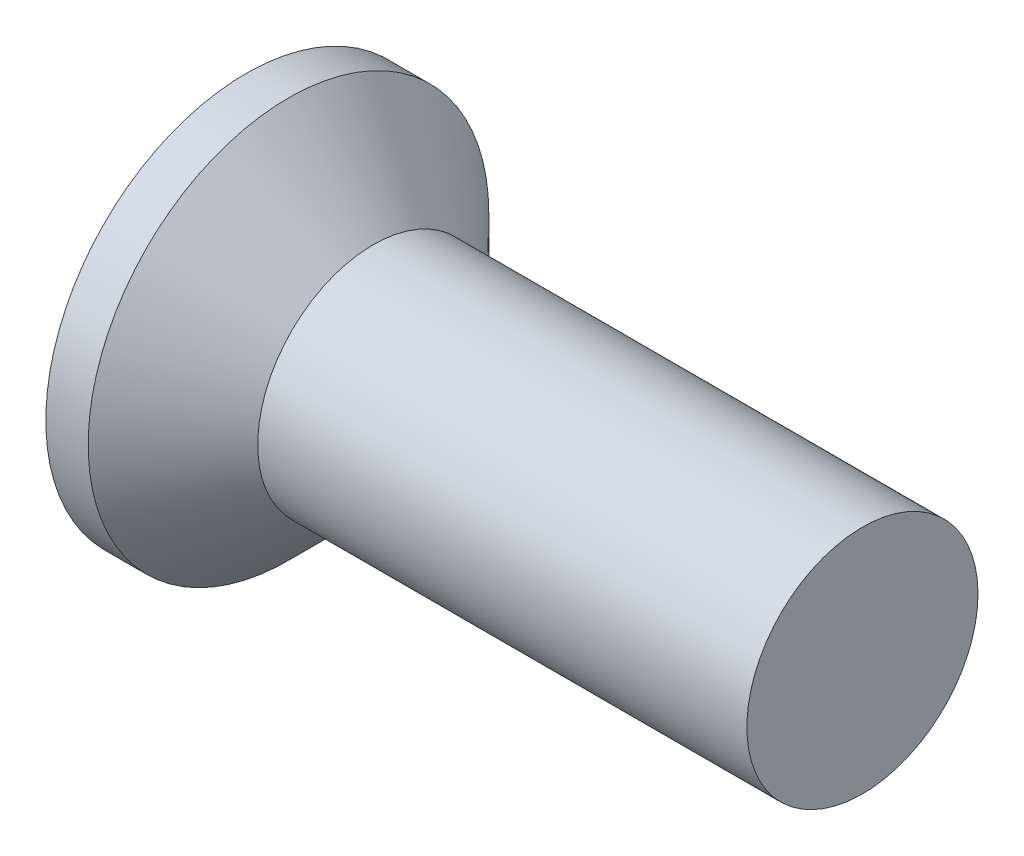
SolidWorks part; units mm, degrees
ref_plane "Front" through (0, 0, 0) normal (0, 0, 1) x (1, 0, 0)
ref_plane "Top" through (0, 0, 0) normal (0, 1, 0) x (1, 0, 0)
ref_plane "Right" through (0, 0, 0) normal (1, 0, 0) x (0, 0, -1)
sketch "Sketch1" plane through (0, 0, 0) normal (0, 0, 1) x (1, 0, 0)
  line L0 (8, 1.5) -> (2.65, 1.5)
  line L1 (2.65, 1.5) -> (1.65, 1.5)
  line L2 (1.65, 1.5) -> (0.55, 2.6)
  line L3 (0.55, 2.6) -> (0, 2.6)
  line L4 (8, 1.5) -> (8, 0)
  line L5 (4.5158, 0) -> (-89.8219, 0) construction
  line L6 (8, 0) -> (0, 0)
  line L7 (0, 2.6) -> (0, 0)
  dimension "D1" = 45
  dimension "d" = 3
  dimension "dk" = 5.2
  dimension "l" = 8
  dimension "k" = 1.65
  dimension "a" = 1
revolve "Base" add sketch "Sketch1" angle 360 about L5
cosmetic thread "ThreadCosmetic1" [suppressed] parameters "bb"=6.35, "THD_MINOR"=2.459
sketch "Sketch6" plane through (0, 0, 0) normal (1, 0, 0) x (0, 0, -1)
  line L0 (-1.9271, 0) -> (2.0512, 0) construction
  line L1 (0, 1.8651) -> (0, -2.0207) construction
  line L2 (0.32, 0.32) -> (0.32, 1.6)
  line L3 (0.32, 1.6) -> (-0.32, 1.6)
  line L4 (-0.32, 0.32) -> (-0.32, 1.6)
  line L5 (0.32, 0.32) -> (1.6, 0.32)
  line L6 (1.6, 0.32) -> (1.6, -0.32)
  line L7 (-1.6, 0.32) -> (-1.6, -0.32)
  line L8 (-0.32, 0.32) -> (-1.6, 0.32)
  line L9 (-0.32, -0.32) -> (-1.6, -0.32)
  line L10 (0.32, -0.32) -> (1.6, -0.32)
  line L11 (-0.32, -0.32) -> (-0.32, -1.6)
  line L12 (0.32, -1.6) -> (-0.32, -1.6)
  line L13 (0.32, -0.32) -> (0.32, -1.6)
  point P16 (-1.6, 0)
  point P17 (1.6, 0)
  dimension "D1" = 0.64
  dimension "m" = 3.2
extrude "CrossRecess" cut sketch "Sketch6" along normal blind 0.825
draft "Draft9" type of draft neutral plane draft angle 30 faces to draft 4 face at (0.4125, 1.6, 0) face at (0.4125, 0, 1.6) face at (0.4125, -1.6, 0) face at (0.4125, 0, -1.6) neutral plane through (0, 2.6, 0) neutral plane normal (-1, 0, 0) parameters "D1"=30
fillet "Fillet5" radius 0.3 4 edges at (0.4125, -0.32, -0.32) (0.4125, 0.32, -0.32) (0.4125, 0.32, 0.32) (0.4125, -0.32, 0.32)
sketch "Sketch7" plane through (0, 0, 0) normal (1, 0, 0) x (0, 0, -1)
  line L0 (-2.0126, 0) -> (1.9757, 0) construction
  line L1 (0, 1.9314) -> (0, -2.0126) construction
  line L2 (0, 0) -> (1.5555, 1.5555) construction
  line L3 (0, 0.4782) -> (1.1314, 1.1314)
  line L4 (-1.5402, 1.5402) -> (0, 0) construction
  line L5 (0.4782, 0) -> (1.1314, 1.1314)
  line L6 (0, -0.4782) -> (1.1314, -1.1314)
  line L7 (0.4782, 0) -> (1.1314, -1.1314)
  line L8 (-0.4782, 0) -> (-1.1314, -1.1314)
  line L9 (0, -0.4782) -> (-1.1314, -1.1314)
  line L10 (-0.4782, 0) -> (-1.1314, 1.1314)
  line L11 (0, 0.4782) -> (-1.1314, 1.1314)
  dimension "D3" = 15
extrude "Cut-Extrude3" [suppressed] cut sketch "Sketch7" along normal blind 10 draft 20
sketch "Sketch8" plane through (0, 0, 0) normal (0, 0, 1) x (1, 0, 0)
  line L0 (-17, 1.7705) -> (-18.25, 1.5)
  line L1 (-18.25, 1.5) -> (1.65, 1.5)
  line L3 (8, -1.5) -> (8, 1.5) construction
  line L6 (1.65, 1.5) -> (1.65, 6.5)
  line L7 (1.65, 6.5) -> (-17, 6.5)
  line L8 (-17, 6.5) -> (-17, 1.7705)
  line L9 (62.4753, 0.2705) -> (52.9594, 0.2705) construction
  dimension "D1" = 5
  dimension "x" = 1.25
  dimension "b" = 25
sketch "Sketch9" plane through (0, 0, 0) normal (0, 0, 1) x (1, 0, 0)
  line L0 (8, 1.2657) -> (8.1353, 1.5)
  line L1 (8.1353, 1.5) -> (8.1353, 1.7705)
  line L2 (8.1353, 1.7705) -> (7.8647, 1.7705)
  line L3 (7.8647, 1.7705) -> (7.8647, 1.5)
  line L4 (7.8647, 1.5) -> (8, 1.2657)
  line L5 (0, 0) -> (73.843, 0) construction
  line L6 (8, -1.5) -> (8, 1.5) construction
  dimension "D1" = 3
  dimension "D2" = 0.2705
revolve "Cut-Revolve10" [suppressed] cut sketch "Sketch9" angle 360 about L5
pattern_linear "LPattern10" [suppressed] count 20 spacing 0.3246 along (1, 0, 0)
equation "\"D1@Sketch6\" = \"m@Sketch6\" / 5"
equation "\"D1@CrossRecess\" = \"k@Sketch1\" / 2"
equation "\"D1@Sketch9\" = \"d@Sketch1\""
equation "\"D2@Sketch9\" =  ( \"d@Sketch1\" - \"THD_MINOR@ThreadCosmetic1\" )  / 2"
equation "\"D3@LPattern10\" = \"D2@Sketch9\" * 1.2"
equation "\"D1@LPattern10\" = \"bb@ThreadCosmetic1\" / \"D3@LPattern10\" "
